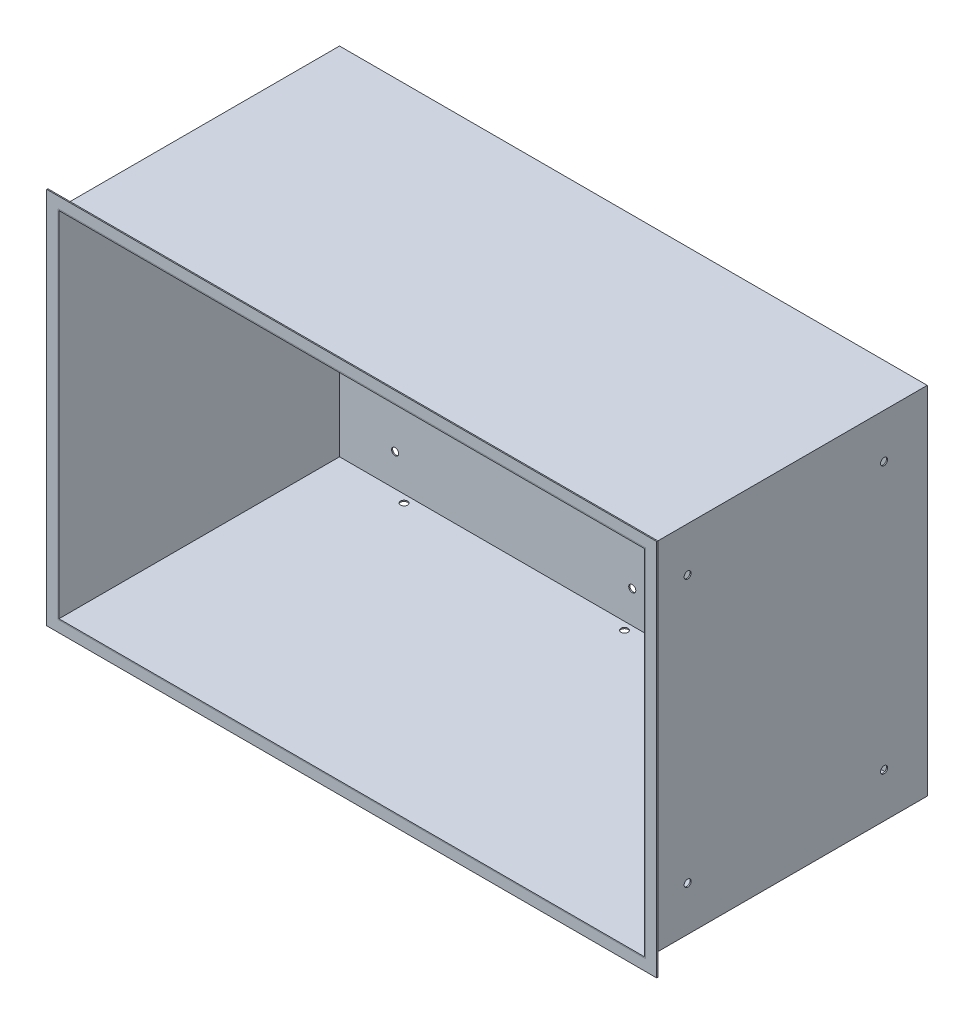
SolidWorks part; units mm, degrees
ref_plane "Alzado" through (0, 0, 0) normal (0, 0, 1) x (1, 0, 0)
ref_plane "Planta" through (0, 0, 0) normal (0, 1, 0) x (1, 0, 0)
ref_plane "Vista lateral" through (0, 0, 0) normal (1, 0, 0) x (0, 0, -1)
sketch "Croquis1" plane through (0, 0, 0) normal (0, 1, 0) x (1, 0, 0)
  line L1 (-396.5, 190) -> (396.5, 190)
  line L2 (-396.5, 190) -> (-396.5, -190)
  line L3 (-396.5, -190) -> (396.5, -190)
  line L4 (396.5, 190) -> (396.5, -190)
  line L5 (-396.5, 190) -> (396.5, -190) construction
  line L6 (-396.5, -190) -> (396.5, 190) construction
  point P0 (0, 0)
  dimension "D1" = 380
  dimension "D2" = 793
extrude "Saliente-Extruir1" add sketch "Croquis1" along normal blind 480
shell "Vaciado1" thickness 1.52
sketch "Croquis2" plane through (0, 0, 190) normal (0, 0, 1) x (1, 0, 0)
  line L0 (-396.5, 480) -> (-396.5, 0)
  line L1 (-396.5, 0) -> (396.5, 0)
  line L2 (396.5, 0) -> (396.5, 480)
  line L3 (396.5, 480) -> (-396.5, 480)
  line L4 (-411.5, 495) -> (-411.5, -15)
  line L5 (-411.5, -15) -> (411.5, -15)
  line L6 (411.5, -15) -> (411.5, 495)
  line L7 (411.5, 495) -> (-411.5, 495)
  dimension "D1" = 15
extrude "Saliente-Extruir2" add sketch "Croquis2" against normal blind 1.52 separate body
sketch "Croquis3" plane through (396.5, 0, 0) normal (1, 0, 0) x (0, 0, -1)
  line L0 (-142.7327, 480) -> (-133.26, 420) construction
  line L1 (-190, 480) -> (190, 480) construction
  line L2 (-133.26, 420) -> (131.74, 420) construction
  line L3 (131.74, 420) -> (131.74, 480) construction
  line L4 (-133.26, 420) -> (-133.26, 60) construction
  line L5 (-133.26, 60) -> (131.74, 60) construction
  line L6 (-133.26, 240) -> (-37.3811, 240) construction
  circle A0 centre (131.74, 60) radius 4.765
  circle A1 centre (-133.26, 60) radius 4.7625
  circle A2 centre (131.74, 420) radius 4.765
  circle A3 centre (-133.26, 420) radius 4.7625
  dimension "D1" = 9.525
  dimension "D2" = 9.53
extrude "Cortar-Extruir1" cut sketch "Croquis3" against normal blind 10
sketch "Croquis4" plane through (0, 0, -188.48) normal (0, 0, 1) x (1, 0, 0)
  circle A0 centre (-320, 435) radius 4.765
  circle A1 centre (-320, 240) radius 4.7625
  circle A2 centre (-320, 45) radius 4.765
  circle A3 centre (320, 45) radius 4.765
  circle A4 centre (320, 435) radius 4.765
  circle A5 centre (320, 240) radius 4.7625
  circle A6 centre (0, 45) radius 4.765
  circle A7 centre (0, 435) radius 4.765
extrude "Cortar-Extruir2" cut sketch "Croquis4" against normal blind 10
sketch "Croquis5" plane through (0, 0, 0) normal (0, -1, 0) x (1, 0, 0)
  line L0 (-396.5, -190) -> (-396.5, -178) construction
  line L1 (-396.5, -190) -> (-396.5, 190) construction
  line L2 (-396.5, -178) -> (396.5, -178) construction
  line L3 (396.5, 190) -> (396.5, -190) construction
  line L4 (396.5, -178) -> (0, -178) construction
  line L5 (0, -178) -> (198.25, -178) construction
  line L6 (0, -178) -> (-396.5, -178) construction
  line L7 (-396.5, -178) -> (-198.25, -178) construction
  line L8 (-198.25, -178) -> (-396.5, -178) construction
  line L9 (-396.5, -178) -> (-297.375, -178) construction
  line L10 (198.25, -178) -> (396.5, -178) construction
  line L11 (396.5, -178) -> (297.375, -178) construction
  circle A0 centre (-297.375, -178) radius 4.7625
  circle A1 centre (0, -178) radius 4.7625
  circle A2 centre (297.375, -178) radius 4.7625
  dimension "D2" = 9.525
  dimension "D3" = 9.525
  dimension "D4" = 9.525
  dimension "D1" = 12
extrude "Cortar-Extruir3" cut sketch "Croquis5" against normal blind 10
sketch "Croquis6" plane through (0, 0, 0) normal (0, -1, 0) x (1, 0, 0)
  line L1 (372.5, -75.1) -> (372.5, -50.1) construction
  line L2 (372.5, -24.7) -> (372.5, 0.3) construction
  line L3 (372.5, -100.5) -> (385.2, -100.5) construction
  line L4 (372.5, -190) -> (372.5, -100.5) construction
  line L5 (396.5, -190) -> (-396.5, -190) construction
  line L6 (372.5, -100.5) -> (396.5, -100.5) construction
  line L7 (396.5, 190) -> (396.5, -190) construction
  circle A0 centre (372.5, -87.8) radius 12.7
  circle A1 centre (372.5, -37.4) radius 12.7
  circle A2 centre (372.5, 13) radius 12.7
  dimension "D2" = 25.4
  dimension "D5" = 25.4
  dimension "D6" = 25.4
  dimension "D3" = 25
  dimension "D4" = 25
  dimension "D7" = 89.5
  dimension "D8" = 24
extrude "Cortar-Extruir4" cut sketch "Croquis6" against normal blind 10
